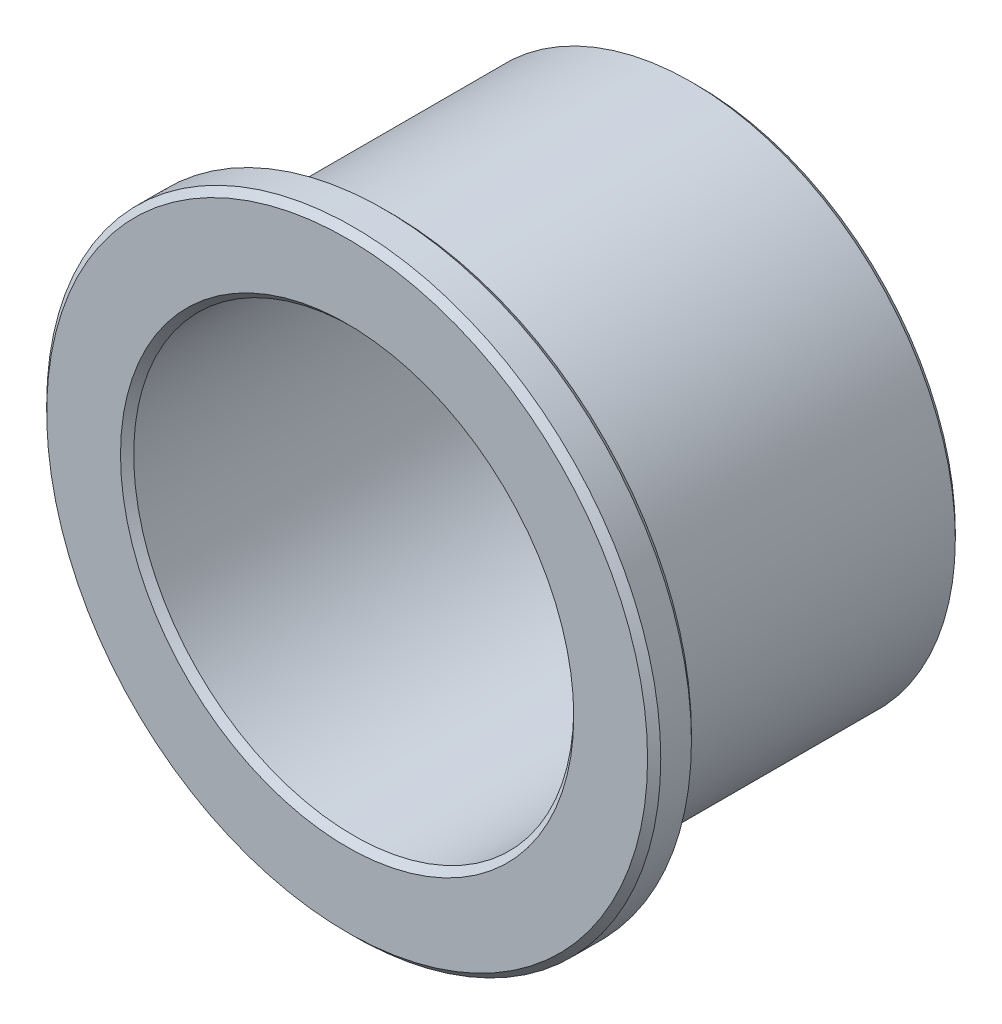
SolidWorks part; units mm, degrees
material "Commercial Bronze, UNS C22000 (90-10 Bronze)"
ref_plane "Front" through (0, 0, 0) normal (0, 0, 1) x (1, 0, 0)
ref_plane "Top" through (0, 0, 0) normal (0, 1, 0) x (1, 0, 0)
ref_plane "Right" through (0, 0, 0) normal (1, 0, 0) x (0, 0, -1)
sketch "Sketch1" plane through (0, 0, 0) normal (0, 0, 1) x (1, 0, 0)
  circle A0 centre (0, 0) radius 7.9629
  circle A1 centre (0, 0) radius 9.5504
  circle A2 centre (0, 0) radius 11.1125
  dimension "ID" = 15.9258
  dimension "OD" = 19.1008
  dimension "Flange OD" = 22.225
sketch "Sketch2" plane through (0, 0, 0) normal (1, 0, 0) x (0, 0, -1)
  line L0 (-6.35, -11.1125) -> (6.35, -11.1125) construction
  line L1 (0, 11.1125) -> (0, -11.1125) construction
  line L3 (-4.7625, 9.5504) -> (6.35, 9.5504) construction
  point P3 (0, -11.1125)
  point P7 (0, 9.5504)
  point P9 (-4.7625, -11.1125)
  point P10 (-6.35, 11.1125)
  point P23 (0, 11.1125)
  dimension "Flange Thickness" = 1.5875
  dimension "Length" = 12.7
sketch "Sketch3" plane through (0, 0, 0) normal (0, 0, 1) x (1, 0, 0)
  circle A0 centre (0, 0) radius 11.1125 construction
  circle A1 centre (0, 0) radius 11.1125
  circle A2 centre (0, 0) radius 7.9629 construction
  circle A3 centre (0, 0) radius 7.9629
extrude "Boss-Extrude1" add sketch "Sketch3" against normal up to vertex (-4.7625 mm away) from vertex at 6.35 starting at point (0, -11.1125, 6.35)
sketch "Sketch4" plane through (0, 0, 0) normal (0, 0, 1) x (1, 0, 0)
  circle A0 centre (0, 0) radius 7.9629 construction
  circle A1 centre (0, 0) radius 9.5504 construction
  circle A2 centre (0, 0) radius 7.9629
  circle A3 centre (0, 0) radius 9.5504
extrude "Boss-Extrude2" add sketch "Sketch4" against normal up to vertex (6.35 mm away) from vertex at 4.7625 starting at point (0, -11.1125, 4.7625)
chamfer "Chamfer1" distance 0.2389 angle 45 6 edges at (7.9629, 0, 6.35) (11.1125, 0, 6.35) (11.1125, 0, 4.7625) (9.5504, 0, 4.7625) (7.9629, 0, -6.35) (9.5504, 0, -6.35)
equation "\"D1@Chamfer1\"=\"ID@Sketch1\"*0.015"
